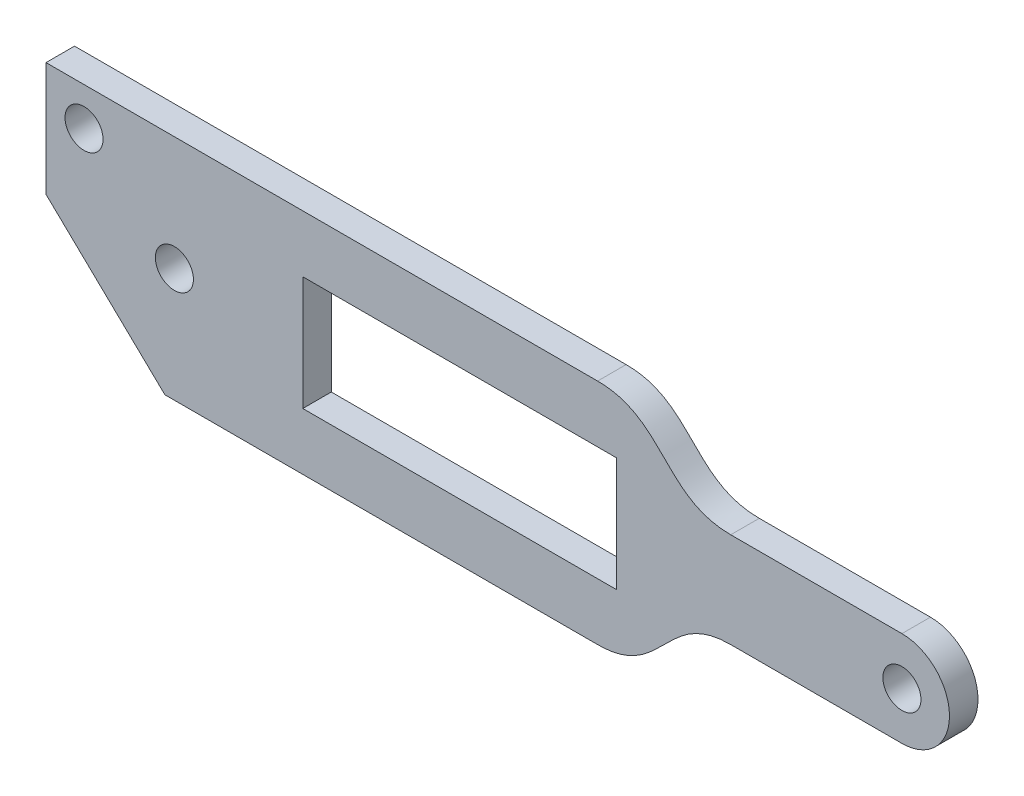
SolidWorks part; units mm, degrees
ref_plane "Plan de face" through (0, 0, 0) normal (0, 0, 1) x (1, 0, 0)
ref_plane "Plan de dessus" through (0, 0, 0) normal (0, 1, 0) x (1, 0, 0)
ref_plane "Plan de droite" through (0, 0, 0) normal (1, 0, 0) x (0, 0, -1)
sketch "Esquisse1" plane through (0, 0, 0) normal (0, 0, 1) x (1, 0, 0)
  line L0 (-47.5, 0) -> (-35, -12)
  line L1 (47.5, -12) -> (-47.5, -12)
  line L2 (47.5, -12) -> (47.5, 12)
  line L3 (47.5, 12) -> (-47.5, 12)
  line L4 (-47.5, -12) -> (-47.5, 12)
  line L5 (-20.5, 6) -> (-20.5, -6)
  line L6 (47.5, 12) -> (-47.5, -12) construction
  line L7 (24.5, 5) -> (17.5, 5) construction
  line L8 (47.5, -12) -> (17.5, -12)
  line L9 (47.5, -12) -> (47.5, -5)
  line L10 (47.5, -5) -> (17.5, -5)
  line L11 (17.5, -12) -> (17.5, -5)
  line L12 (47.5, 5) -> (17.5, 5)
  line L13 (47.5, 5) -> (47.5, 12)
  line L14 (47.5, 12) -> (17.5, 12)
  line L15 (17.5, 5) -> (17.5, 12)
  line L16 (-20.5, 6) -> (12.5, 6)
  line L18 (-20.5, -6) -> (12.5, -6)
  line L19 (12.5, 6) -> (12.5, -6)
  line L20 (17.5, 5) -> (17.5, 12) construction
  line L21 (17.5, 12) -> (10.5, 12) construction
  line L22 (24.5, -5) -> (17.5, -5) construction
  line L23 (17.5, -5) -> (17.5, -12) construction
  line L24 (17.5, -12) -> (10.5, -12) construction
  line L25 (-47.5, 0) -> (-20.5, 0) construction
  circle A0 centre (42.5, 0) radius 2
  circle A1 centre (-34, 0) radius 2
  circle A2 centre (42.5, 0) radius 5
  circle A3 centre (-43.5, 8) radius 2
  spline S0 degree 3 poles (24.5, 5) (17.5, 5) (17.5, 12) (10.5, 12) knots 0 0 0 0 1 1 1 1
  spline S1 degree 3 poles (24.5, -5) (17.5, -5) (17.5, -12) (10.5, -12) knots 0 0 0 0 1 1 1 1
  point P0 (0, 0)
  dimension "D12" = 7
  dimension "D13" = 4
  dimension "D8" = 4
  dimension "D14" = 4
  dimension "D1" = 24
  dimension "D2" = 95
  dimension "D3" = 30
  dimension "D4" = 7
  dimension "D5" = 30
  dimension "D6" = 7
  dimension "D7" = 33
  dimension "D9" = 6
  dimension "D10" = 5
  dimension "D11" = 7
  dimension "D15" = 4
  dimension "D16" = 4
extrude "Boss.-Extru.1" add sketch "Esquisse1" along normal blind 3 contours S1 L11 L10 A2 L12 L15 S0 L3 L4 L0 L1 L16 L19 L18 L5 | L12 S0 L15 | S1 L10 L11 | A2
